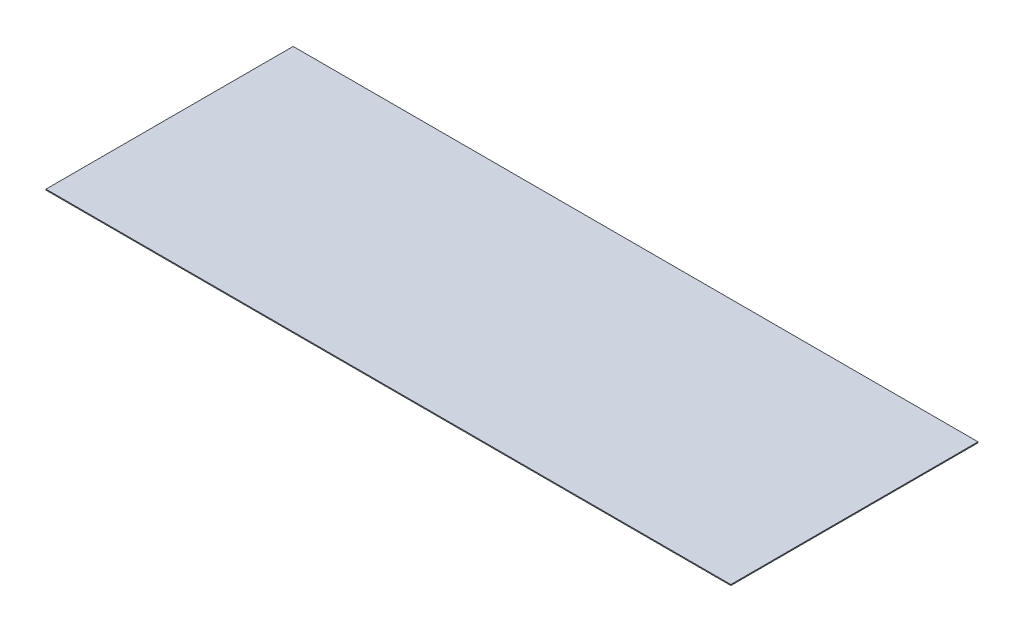
SolidWorks part; units mm, degrees
ref_plane "Front Plane" through (0, 0, 0) normal (0, 0, 1) x (1, 0, 0)
ref_plane "Top Plane" through (0, 0, 0) normal (0, 1, 0) x (1, 0, 0)
ref_plane "Right Plane" through (0, 0, 0) normal (1, 0, 0) x (0, 0, -1)
sketch "Sketch1" plane through (0, 0, 0) normal (0, 1, 0) x (1, 0, 0)
  line L1 (-527.1447, 240.749) -> (622.8553, 240.749)
  line L2 (-527.1447, 240.749) -> (-527.1447, -174.251)
  line L3 (-527.1447, -174.251) -> (622.8553, -174.251)
  line L4 (622.8553, 240.749) -> (622.8553, -174.251)
  dimension "D1" = 1150
  dimension "D2" = 415
extrude "Boss-Extrude1" add sketch "Sketch1" along normal blind 1.5875
sketch "Sketch2" plane through (0, 1.5875, 0) normal (0, 1, 0) x (1, 0, 0)
  line L0 (-520.0524, 240.749) -> (-520.0524, 237.1918)
  line L1 (622.8553, 240.749) -> (-527.1447, 240.749) construction
  line L2 (-523.0991, 234.145) -> (-527.1447, 234.145)
  line L3 (-527.1447, 240.749) -> (-527.1447, -174.251) construction
  circle A0 centre (-520.0524, 234.145) radius 3.0468
